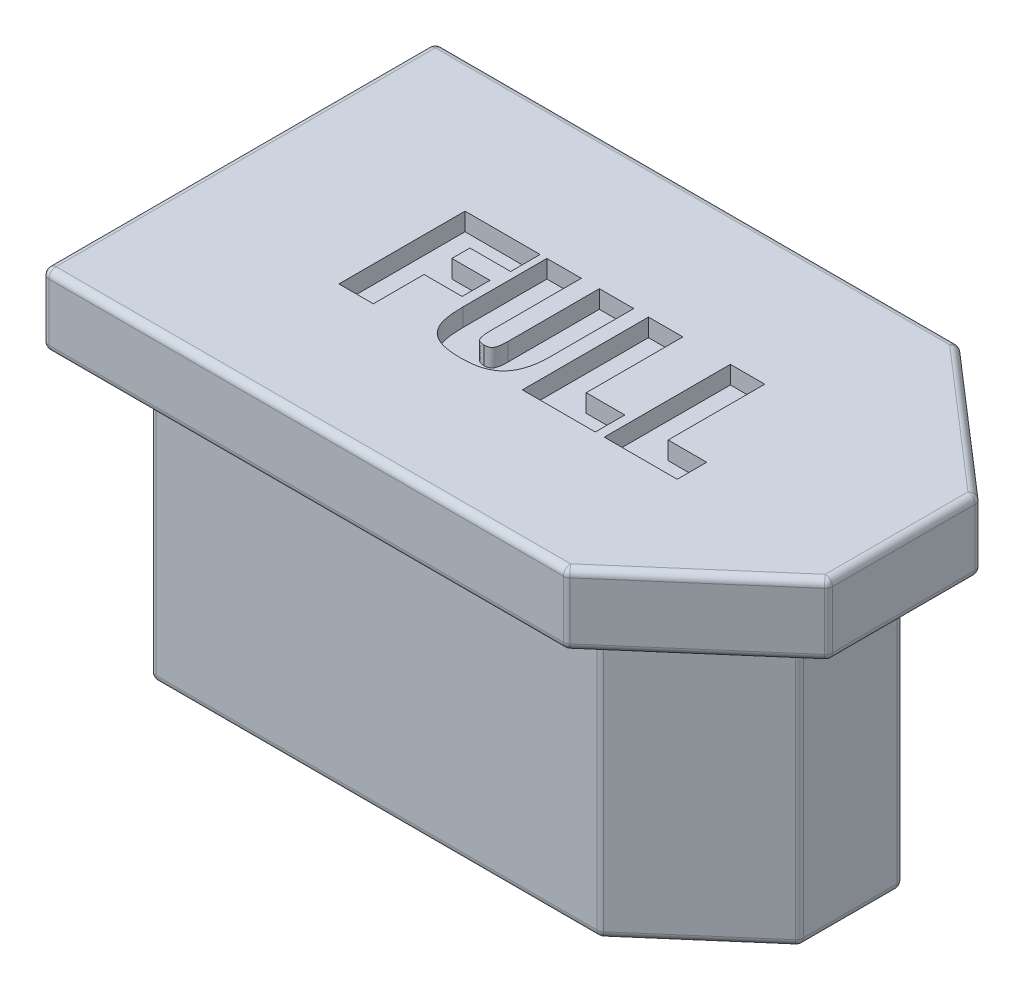
SolidWorks part; units mm, degrees
ref_plane "Front Plane" through (0, 0, 0) normal (0, 0, 1) x (1, 0, 0)
ref_plane "Top Plane" through (0, 0, 0) normal (0, 1, 0) x (1, 0, 0)
ref_plane "Right Plane" through (0, 0, 0) normal (1, 0, 0) x (0, 0, -1)
sketch "Sketch1" plane through (0, 0, 0) normal (0, 1, 0) x (1, 0, 0)
  line L0 (-7.8002, 4) -> (4.7998, 4)
  line L1 (4.7998, 4) -> (7.8002, 1.4)
  line L2 (7.8002, 1.4) -> (7.8002, -1.4)
  line L3 (7.8002, -1.4) -> (4.7998, -4)
  line L4 (4.7998, -4) -> (-7.8002, -4)
  line L5 (-7.8002, -4) -> (-7.8002, 4)
  line L6 (-7.8002, 0) -> (7.8002, 0) construction
  dimension "D1" = 8
  dimension "D2" = 12.6
  dimension "D3" = 139.09
  dimension "D4" = 2.8
extrude "Boss-Extrude1" add sketch "Sketch1" along normal mid plane 8
shell "Shell1" thickness 0.8
sketch "Sketch2" plane through (0, 4, 0) normal (0, 1, 0) x (1, 0, 0)
  line L0 (-7.8002, 4) -> (-7.8002, -4) construction
  line L1 (4.7998, 4) -> (-7.8002, 4) construction
  line L2 (7.8002, 1.4) -> (4.7998, 4) construction
  line L3 (7.8002, -1.4) -> (7.8002, 1.4) construction
  line L4 (4.7998, -4) -> (7.8002, -1.4) construction
  line L5 (-7.8002, -4) -> (4.7998, -4) construction
  line L6 (-7.8002, 4) -> (-7.8002, -4) construction
  line L7 (4.7998, 4) -> (-7.8002, 4) construction
  line L8 (7.8002, 1.4) -> (4.7998, 4) construction
  line L9 (7.8002, -1.4) -> (7.8002, 1.4) construction
  line L10 (4.7998, -4) -> (7.8002, -1.4) construction
  line L11 (-7.8002, -4) -> (4.7998, -4) construction
  line L12 (-9.3002, 5.5) -> (-9.3002, -5.5)
  line L13 (-9.3002, -5.5) -> (5.3593, -5.5)
  line L14 (5.3593, -5.5) -> (9.3002, -2.085)
  line L15 (9.3002, -2.085) -> (9.3002, 2.085)
  line L16 (9.3002, 2.085) -> (5.3593, 5.5)
  line L17 (5.3593, 5.5) -> (-9.3002, 5.5)
  dimension "D1" = 1.5
extrude "Boss-Extrude2" add sketch "Sketch2" along normal blind 2
sketch "Sketch4" plane through (0, -4, 0) normal (0, -1, 0) x (1, 0, 0)
  line L0 (-1.0002, -3.2) -> (-1.0002, -2)
  line L3 (4.5014, -3.2) -> (-7.0002, -3.2) construction
  line L5 (-1.0002, -2) -> (0.9998, -2)
  line L6 (0.9998, -2) -> (0.9998, -3.2)
  line L7 (-1.0002, -3.2) -> (0.9998, -3.2)
  dimension "D1" = 1.2
  dimension "D2" = 2
  dimension "D3" = 6
extrude "Boss-Extrude4" add sketch "Sketch4" against normal up to next
sketch "Sketch5" plane through (0, 4, 0) normal (0, -1, 0) x (1, 0, 0)
  line L0 (-0.5502, -2) -> (-0.5502, 2)
  line L1 (0.9998, -2) -> (-1.0002, -2) construction
  line L2 (-0.5502, 2) -> (0.5498, 2)
  line L3 (0.5498, 2) -> (0.5498, -2)
  line L4 (0.9998, -2) -> (-1.0002, -2) construction
  line L5 (0.5498, -2) -> (-0.5502, -2)
  line L6 (-0.0002, -2) -> (-0.0002, 2) construction
  dimension "D1" = 4
  dimension "D2" = 1.1
extrude "Cut-Extrude1" cut sketch "Sketch5" against normal blind 1
fillet "Fillet1" radius 0.2 78 edges at (4.5014, 0, -3.2) (7.0002, 0, -1.0347) (7.0002, 0, 1.0347) (4.5014, 0, 3.2) (-7.0002, 0, -3.2) (-1.0002, 0, -3.2) (-1.0002, 0, -2) (0.9998, 0, -2) (0.9998, 0, -3.2) (-7.0002, 0, 3.2) (0.9998, 4, -2.6) (0.9998, -4, -2.6) (2.7506, -4, -3.2) (-1.0002, 4, -2.6) (-1.0002, -4, -2.6) (-0.0002, 4, 2) (5.7508, -4, -2.1173) (-4.0002, -4, -3.2) (-0.0002, -4, -2) (-0.0002, 5, 2) (0.5498, 4.5, 2) (-0.5502, 4.5, 2) (0.5498, 5, 0) (-0.5502, 5, 0) (5.7508, 4, -2.1173) (2.7506, 4, -3.2) (-0.0002, 5, -2) (-4.0002, 4, -3.2) (7.0002, -4, 0) (7.0002, 4, 0) (-1.2494, -4, 3.2) (-1.2494, 4, 3.2) (5.7508, -4, 2.1173) (5.7508, 4, 2.1173) (-7.0002, -4, 0) (-7.0002, 4, 0) (-1.9705, 4, -5.5) (-9.3002, 4, 0) (-1.9705, 4, 5.5) (7.3297, 4, 3.7925) (9.3002, 4, 0) (7.3297, 4, -3.7925) (-1.9705, 6, -5.5) (-9.3002, 6, 0) (-1.9705, 6, 5.5) (7.3297, 6, 3.7925) (9.3002, 6, 0) (7.3297, 6, -3.7925) (5.3593, 5, -5.5) (9.3002, 5, -2.085) (9.3002, 5, 2.085) (5.3593, 5, 5.5) (-9.3002, 5, 5.5) (-9.3002, 5, -5.5) (-7.8002, -4, 0) (6.3, -4, 2.7) (7.8002, -4, 0) (6.3, -4, -2.7) (-1.5002, -4, -4) (-7.8002, 4, 0) (-1.5002, 4, 4) (6.3, 4, 2.7) (7.8002, 4, 0) (6.3, 4, -2.7) (-1.5002, 4, -4) (-7.8002, 0, -4) (4.7998, 0, -4) (7.8002, 0, -1.4) (7.8002, 0, 1.4) (4.7998, 0, 4) (-7.8002, 0, 4) (-1.5002, -4, 4)
sketch "Sketch6" plane through (0, 6, 0) normal (0, 1, 0) x (1, 0, 0)
  line L0 (-4.7296, 1.7632) -> (-2.6301, 1.7632)
  line L1 (-2.6301, 1.7632) -> (-2.6301, 0.9388)
  line L2 (-2.6301, 0.9388) -> (-3.7679, 0.9388)
  line L3 (-3.7679, 0.9388) -> (-3.7679, 0.4351)
  line L4 (-3.7679, 0.4351) -> (-2.7045, 0.4351)
  line L5 (-2.7045, 0.4351) -> (-2.7045, -0.3435)
  line L6 (-2.7045, -0.3435) -> (-3.7679, -0.3435)
  line L7 (-3.7679, -0.3435) -> (-3.7679, -1.7632)
  line L8 (-3.7679, -1.7632) -> (-4.7296, -1.7632)
  line L9 (-4.7296, -1.7632) -> (-4.7296, 1.7632)
  line L10 (-0.9743, 1.7632) -> (-0.0125, 1.7632)
  line L11 (-0.0125, 1.7632) -> (-0.0125, -0.5825)
  line L12 (-2.4398, -0.5825) -> (-2.4398, 1.7632)
  line L13 (-2.4398, 1.7632) -> (-1.478, 1.7632)
  line L14 (-1.478, 1.7632) -> (-1.478, -0.7843)
  line L15 (-0.9743, -0.7843) -> (-0.9743, 1.7632)
  line L16 (0.3997, 1.7632) -> (1.3614, 1.7632)
  line L17 (1.3614, 1.7632) -> (1.3614, -0.9388)
  line L18 (1.3614, -0.9388) -> (2.4398, -0.9388)
  line L19 (2.4398, -0.9388) -> (2.4398, -1.7632)
  line L20 (2.4398, -1.7632) -> (0.3997, -1.7632)
  line L21 (0.3997, -1.7632) -> (0.3997, 1.7632)
  line L22 (2.6895, 1.7632) -> (3.6512, 1.7632)
  line L23 (3.6512, 1.7632) -> (3.6512, -0.9388)
  line L24 (3.6512, -0.9388) -> (4.7296, -0.9388)
  line L25 (4.7296, -0.9388) -> (4.7296, -1.7632)
  line L26 (4.7296, -1.7632) -> (2.6895, -1.7632)
  line L27 (2.6895, -1.7632) -> (2.6895, 1.7632)
  line L28 (-4.7296, 0) -> (4.7296, 0) construction
  line L29 (0, 0) -> (0, -0.2478) construction
  spline S0 degree 3 poles (-0.0125, -0.5825) (-0.0131, -0.682) (-0.0189, -0.8273) (-0.05, -1.0125) (-0.0792, -1.1375) (-0.1188, -1.2525) (-0.1665, -1.3579) (-0.2242, -1.4526) (-0.2896, -1.5384) (-0.3657, -1.6142) (-0.4543, -1.6787) (-0.5541, -1.7342) (-0.6663, -1.778) (-0.7893, -1.8135) (-0.9767, -1.8459) (-1.1242, -1.8551) (-1.2261, -1.8548) knots 0 0 0 0 0.147092 0.213813 0.276818 0.336371 0.392915 0.447245 0.499697 0.551716 0.60508 0.661012 0.719774 0.782387 0.849635 1 1 1 1
  spline S1 degree 3 poles (-1.2261, -1.8548) (-1.3357, -1.8536) (-1.4935, -1.8483) (-1.6915, -1.8152) (-1.8181, -1.7837) (-1.9307, -1.7414) (-2.0305, -1.688) (-2.1187, -1.6249) (-2.195, -1.5509) (-2.2592, -1.4658) (-2.313, -1.3708) (-2.3562, -1.2652) (-2.3878, -1.149) (-2.4107, -1.0224) (-2.4346, -0.833) (-2.4391, -0.6846) (-2.4398, -0.5825) knots 0 0 0 0 0.1595 0.228771 0.291434 0.348949 0.403253 0.45542 0.506186 0.557166 0.609816 0.664557 0.722531 0.78463 0.851389 1 1 1 1
  spline S2 degree 3 poles (-1.478, -0.7843) (-1.477, -0.85) (-1.4759, -0.942) (-1.4539, -1.0517) (-1.4352, -1.1126) (-1.4038, -1.1606) (-1.3352, -1.206) (-1.2703, -1.213) (-1.2261, -1.2136) knots 0 0 0 0 0.343474 0.475215 0.581632 0.673592 0.767279 1 1 1 1
  spline S3 degree 3 poles (-1.2261, -1.2136) (-1.182, -1.213) (-1.117, -1.206) (-1.0484, -1.1606) (-1.017, -1.1126) (-0.9984, -1.0517) (-0.9764, -0.942) (-0.9753, -0.85) (-0.9743, -0.7843) knots 0 0 0 0 0.232721 0.326408 0.418368 0.524785 0.656526 1 1 1 1
extrude "Cut-Extrude2" cut sketch "Sketch6" against normal blind 0.5
